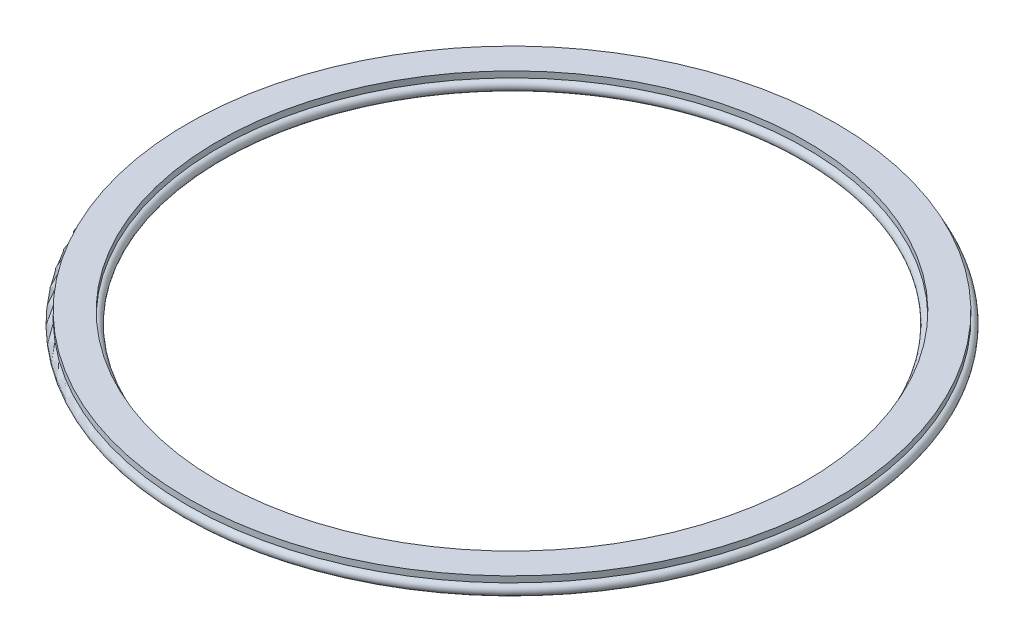
SolidWorks part; units mm, degrees
ref_plane "Front Plane" through (0, 0, 0) normal (0, 0, 1) x (1, 0, 0)
ref_plane "Top Plane" through (0, 0, 0) normal (0, 1, 0) x (1, 0, 0)
ref_plane "Right Plane" through (0, 0, 0) normal (1, 0, 0) x (0, 0, -1)
sketch "Sketch1" plane through (0, 0, 0) normal (0, 0, 1) x (1, 0, 0)
  line L0 (0, 0) -> (320, 0) construction
  line L1 (295, -11) -> (295, -6)
  line L2 (320, 0) -> (290, 0)
  line L3 (320, 0) -> (320, -6)
  line L4 (315, -6) -> (295, -6)
  line L5 (290, 0) -> (290, -6)
  line L6 (315, -11) -> (315, -6)
  line L7 (0, 0) -> (0, -115.1103) construction
  arc A0 (315, -11) -> (320, -6) centre (320, -11) ccw
  arc A1 (290, -6) -> (295, -11) centre (290, -11) ccw
  point P7 (0, 0)
  point P16 (305, -6)
  dimension "D2" = 10
  dimension "D3" = 10
  dimension "D1" = 320
  dimension "D4" = 30
  dimension "D5" = 6
revolve "Revolve1" add sketch "Sketch1" angle 360 about L7
sketch "Sketch2" plane through (0, 0, 0) normal (0, 1, 0) x (1, 0, 0)
  line L0 (0, 320) -> (0, -320) construction
  line L1 (-320, 0) -> (320, 0) construction
  circle A0 centre (0, 0) radius 320 construction
  circle A1 centre (0, 0) radius 320 construction
sketch "Sketch3" plane through (0, 0, 0) normal (0, 0, 1) x (1, 0, 0)
  line L0 (0, 0) -> (305, 0) construction
  line L1 (320, 0) -> (290, 0) construction
sketch "Sketch4" plane through (0, 0, 0) normal (0, 1, 0) x (1, 0, 0)
  circle A0 centre (0, 0) radius 305 construction
ref_plane "Plane1" through (0, -6, 0) normal (0, -1, 0) x (-1, 0, 0)
sketch "Sketch5" plane through (0, -6, 0) normal (0, -1, 0) x (-1, 0, 0)
  circle A0 centre (0, 0) radius 305 construction
  circle A1 centre (0, 0) radius 305
